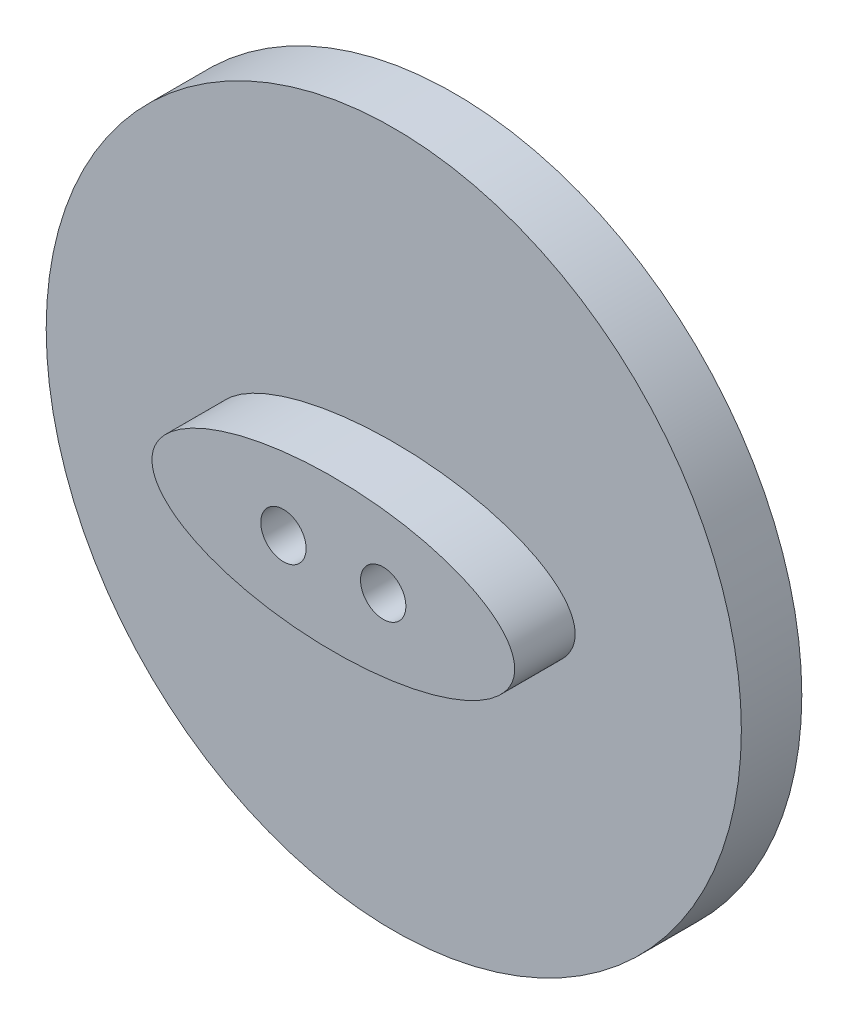
SolidWorks part; units mm, degrees
ref_plane "Plan de face" through (0, 0, 0) normal (0, 0, 1) x (1, 0, 0)
ref_plane "Plan de dessus" through (0, 0, 0) normal (0, 1, 0) x (1, 0, 0)
ref_plane "Plan de droite" through (0, 0, 0) normal (1, 0, 0) x (0, 0, -1)
sketch "Esquisse1" plane through (0, 0, 0) normal (0, 0, 1) x (1, 0, 0)
  circle A1 centre (0, 0) radius 11.5
  dimension "D2" = 23
extrude "Boss.-Extru.1" add sketch "Esquisse1" along normal blind 2 contours A1
sketch "Esquisse6" plane through (0, 0, 2) normal (0, 0, 1) x (1, 0, 0)
  ellipse E0 centre (0, 0) end of major axis (6, 0) minor radius 2.5
extrude "Boss.-Extru.5" add sketch "Esquisse6" along normal blind 2
sketch "Esquisse7" plane through (0, 0, 0) normal (0, 0, -1) x (-1, 0, 0)
  line L0 (1.6505, 0) -> (-1.6505, 0) construction
  line L1 (1.6505, -0.75) -> (-1.6505, -0.75) construction
  line L2 (1.6505, 0.75) -> (-1.6505, 0.75) construction
  arc A1 (1.6505, -0.75) -> (1.6505, 0.75) centre (1.6505, 0) ccw construction
  arc A2 (-1.6505, 0.75) -> (-1.6505, -0.75) centre (-1.6505, 0) ccw construction
  circle A3 centre (-0.799, 0.6694) radius 0.0806 construction
  circle A4 centre (1.6505, 0) radius 0.75
  circle A5 centre (-1.6505, 0) radius 0.75
  point P5 (0, 0)
extrude "Enlèv. mat.-Extru.1" cut sketch "Esquisse7" against normal through all
